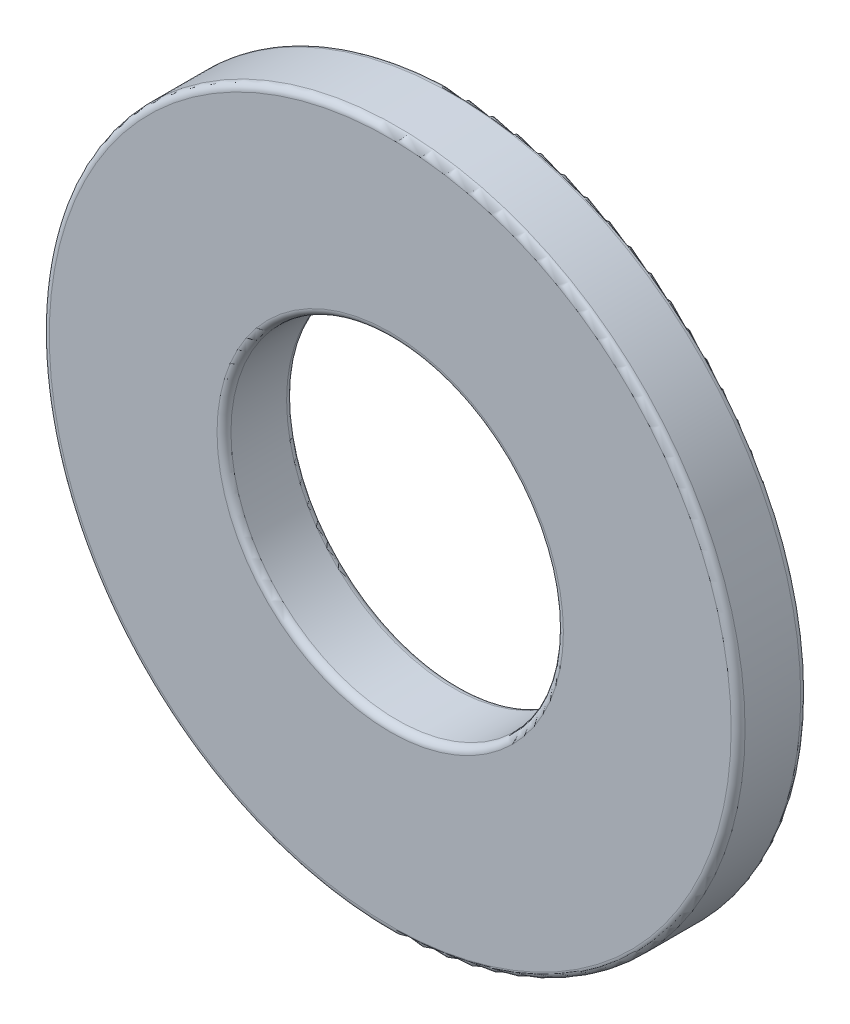
SolidWorks part; units mm, degrees
ref_plane "Front Plane" through (0, 0, 0) normal (0, 0, 1) x (1, 0, 0)
ref_plane "Top Plane" through (0, 0, 0) normal (0, 1, 0) x (1, 0, 0)
ref_plane "Right Plane" through (0, 0, 0) normal (1, 0, 0) x (0, 0, -1)
sketch "Sketch1" plane through (0, 0, 0) normal (0, 0, 1) x (1, 0, 0)
  circle A0 centre (0, 0) radius 4.5 construction
  circle A1 centre (0, 0) radius 2.15 construction
  dimension "OD" = 9
  dimension "ID" = 4.3
sketch "Sketch2" plane through (0, 0, 0) normal (1, 0, 0) x (0, 0, -1)
  line L0 (-0.45, -4.5) -> (0.45, -4.5) construction
  point P0 (0.25, -4.5)
  point P4 (0, -4.5)
  dimension "Thickness Max" = 0.9
  dimension "Thickness Min" = 0.7
sketch "Sketch3" plane through (0, 0, 0) normal (0, 0, 1) x (1, 0, 0)
  circle A0 centre (0, 0) radius 4.5 construction
  circle A1 centre (0, 0) radius 4.5
  circle A2 centre (0, 0) radius 2.15 construction
  circle A3 centre (0, 0) radius 2.15
extrude "Boss-Extrude1" add sketch "Sketch3" against normal up to vertex (0.45 mm away) and the other way up to vertex (0.45 mm away) up to point (0, -4.5, -0.45) other way up to point (0, -4.5, 0.45)
fillet "Fillet1" radius 0.09 4 edges at (4.5, 0, -0.45) (2.15, 0, -0.45) (2.15, 0, 0.45) (4.5, 0, 0.45)
equation "\"D1@Fillet1\" = \"Thickness Max@Sketch2\" * 0.1"
